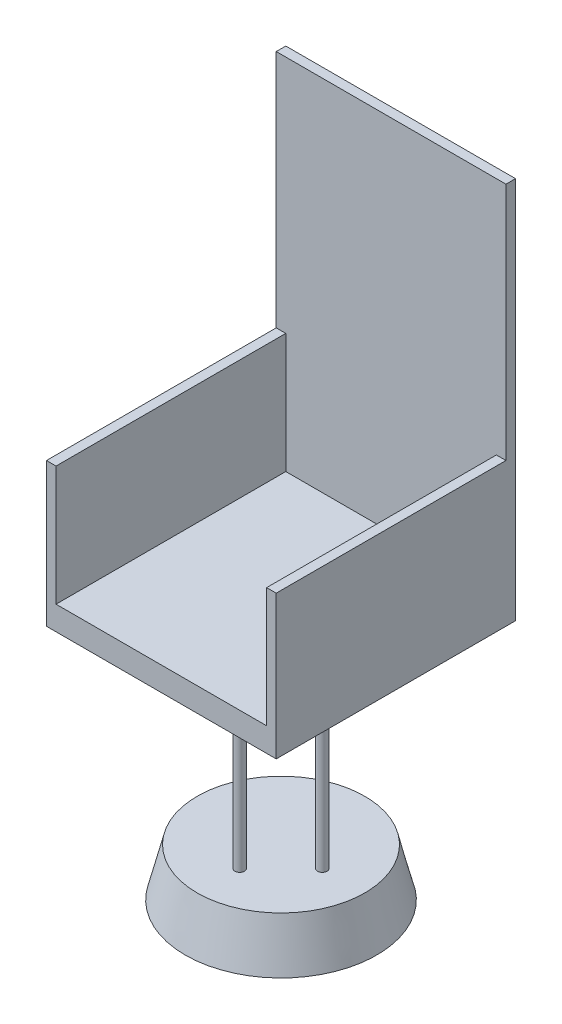
SolidWorks part; units mm, degrees
ref_plane "Front Plane" through (0, 0, 0) normal (0, 0, 1) x (1, 0, 0)
ref_plane "Top Plane" through (0, 0, 0) normal (0, 1, 0) x (1, 0, 0)
ref_plane "Right Plane" through (0, 0, 0) normal (1, 0, 0) x (0, 0, -1)
sketch "Sketch1" plane through (0, 0, 0) normal (0, 1, 0) x (1, 0, 0)
  circle A0 centre (0, 0) radius 200
extrude "Boss-Extrude1" add sketch "Sketch1" along normal blind 100 draft 14 contours A0
sketch "Sketch2" plane through (0, 100, 0) normal (0, 1, 0) x (1, 0, 0)
  circle A1 centre (86.3448, 0) radius 10
  circle A2 centre (0, -86.3448) radius 10
  circle A3 centre (-86.3448, 0) radius 10
  circle A4 centre (0, 86.3448) radius 10
  dimension "D1" = 4
extrude "Boss-Extrude2" add sketch "Sketch2" along normal blind 400
sketch "Sketch7" plane through (0, 500, 0) normal (0, 1, 0) x (1, 0, 0)
  line L1 (-240, 250) -> (240, 250)
  line L2 (-240, 250) -> (-240, -250)
  line L3 (-240, -250) -> (240, -250)
  line L4 (240, 250) -> (240, -250)
  line L5 (-240, 250) -> (240, -250) construction
  line L6 (-240, -250) -> (240, 250) construction
  point P0 (0, 0)
  dimension "D1" = 480
  dimension "D2" = 500
extrude "Boss-Extrude8" add sketch "Sketch7" along normal blind 50
sketch "Sketch8" plane through (0, 550, 0) normal (0, 1, 0) x (1, 0, 0)
  line L0 (240, -250) -> (240, 250) construction
  line L1 (-240, 250) -> (240, 250)
  line L2 (-240, 250) -> (-240, 230)
  line L3 (-240, 230) -> (240, 230)
  line L4 (240, 250) -> (240, 230)
  dimension "D1" = 20
extrude "Boss-Extrude9" add sketch "Sketch8" along normal blind 750
sketch "Sketch9" plane through (0, 550, 0) normal (0, 1, 0) x (1, 0, 0)
  line L0 (-240, -250) -> (240, -250) construction
  line L1 (-240, 230) -> (-220, 230)
  line L2 (-240, 230) -> (-240, -250)
  line L3 (-240, -250) -> (-220, -250)
  line L4 (-220, 230) -> (-220, -250)
  line L6 (240, 230) -> (220, 230)
  line L7 (240, 230) -> (240, -250)
  line L8 (240, -250) -> (220, -250)
  line L9 (220, 230) -> (220, -250)
  dimension "D1" = 20
  dimension "D2" = 20
extrude "Boss-Extrude10" add sketch "Sketch9" along normal blind 250
